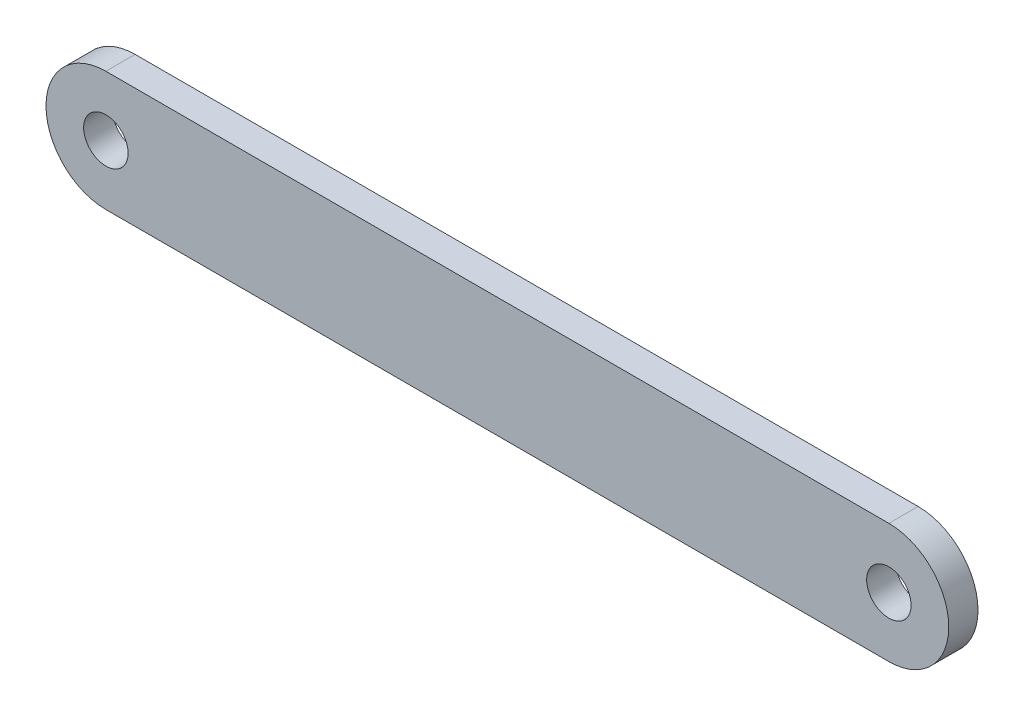
SolidWorks part; units mm, degrees
material "6061 Alloy"
ref_plane "Front Plane" through (0, 0, 0) normal (0, 0, 1) x (1, 0, 0)
ref_plane "Top Plane" through (0, 0, 0) normal (0, 1, 0) x (1, 0, 0)
ref_plane "Right Plane" through (0, 0, 0) normal (1, 0, 0) x (0, 0, -1)
sketch "Sketch1" plane through (0, 0, 0) normal (0, 0, 1) x (1, 0, 0)
  line L0 (-42.5, 0) -> (42.5, 0) construction
  line L1 (-42.5, 6.5) -> (42.5, 6.5)
  line L2 (-42.5, -6.5) -> (42.5, -6.5)
  arc A0 (-42.5, 6.5) -> (-42.5, -6.5) centre (-42.5, 0) ccw
  arc A1 (42.5, -6.5) -> (42.5, 6.5) centre (42.5, 0) ccw
  circle A2 centre (-42.5, 0) radius 2.413
  circle A3 centre (42.5, 0) radius 2.413
  point P2 (0, 0)
  dimension "D1" = 4.826
  dimension "D2" = 85
  dimension "D3" = 13
extrude "Boss-Extrude1" add sketch "Sketch1" along normal blind 3.175
